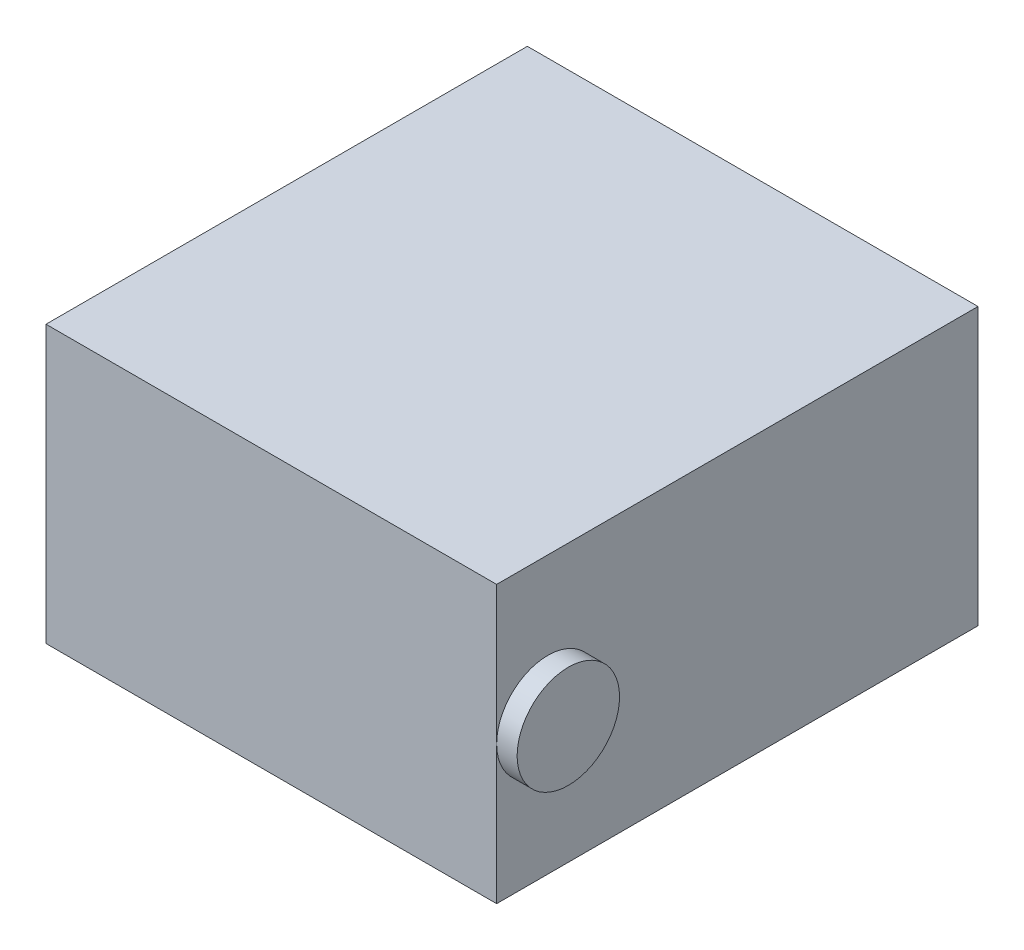
SolidWorks part; units mm, degrees
ref_plane "Front Plane" through (0, 0, 0) normal (0, 0, 1) x (1, 0, 0)
ref_plane "Top Plane" through (0, 0, 0) normal (0, 1, 0) x (1, 0, 0)
ref_plane "Right Plane" through (0, 0, 0) normal (1, 0, 0) x (0, 0, -1)
sketch "Sketch1" plane through (0, 0, 0) normal (0, 1, 0) x (1, 0, 0)
  line L1 (0, 0) -> (139.7, 0)
  line L2 (0, 0) -> (0, 149.225)
  line L3 (0, 149.225) -> (139.7, 149.225)
  line L4 (139.7, 0) -> (139.7, 149.225)
  dimension "D1" = 149.225
  dimension "D2" = 139.7
extrude "Boss-Extrude1" add sketch "Sketch1" along normal blind 85.725
sketch "Sketch2" plane through (0, 0, 0) normal (-1, 0, 0) x (0, 0, 1)
  line L0 (0, 85.725) -> (0, 0) construction
  line L1 (-53.975, 53.975) -> (-6.35, 53.975)
  line L2 (-53.975, 53.975) -> (-53.975, 31.75)
  line L3 (-53.975, 31.75) -> (-6.35, 31.75)
  line L4 (-6.35, 53.975) -> (-6.35, 31.75)
  point P6 (-6.35, 42.8625)
  dimension "D1" = 6.35
  dimension "D2" = 53.975
  dimension "D3" = 22.225
  dimension "D4" = 42.8625
extrude "Boss-Extrude2" add sketch "Sketch2" along normal blind 6.35
sketch "Sketch3" plane through (139.7, 0, 0) normal (1, 0, 0) x (0, 0, -1)
  line L0 (0, 85.725) -> (0, 0) construction
  circle A0 centre (15.875, 42.8625) radius 15.875
  point P6 (0, 42.8625)
  dimension "D1" = 31.75
extrude "Boss-Extrude3" add sketch "Sketch3" along normal blind 6.35
sketch "Sketch4" plane through (0, 0, 0) normal (-1, 0, 0) x (0, 0, 1)
  line L0 (-149.225, 85.725) -> (0, 85.725) construction
  line L1 (0, 85.725) -> (0, 0) construction
  circle A0 centre (-6.35, 79.375) radius 1.5875
  circle A1 centre (-142.875, 79.375) radius 1.5875
  circle A2 centre (-142.875, 15.875) radius 1.5875
  circle A3 centre (-30.1625, 6.35) radius 1.5875
  point P13 (0, 0)
  dimension "D1" = 3.175
  dimension "D2" = 6.35
  dimension "D3" = 6.35
  dimension "D4" = 6.35
  dimension "D5" = 15.875
  dimension "D6" = 30.1625
  dimension "D7" = 6.35
extrude "Cut-Extrude1" cut sketch "Sketch4" against normal blind 6.35
equation "\"D4@Sketch2\"=(3+3/8)/2"
